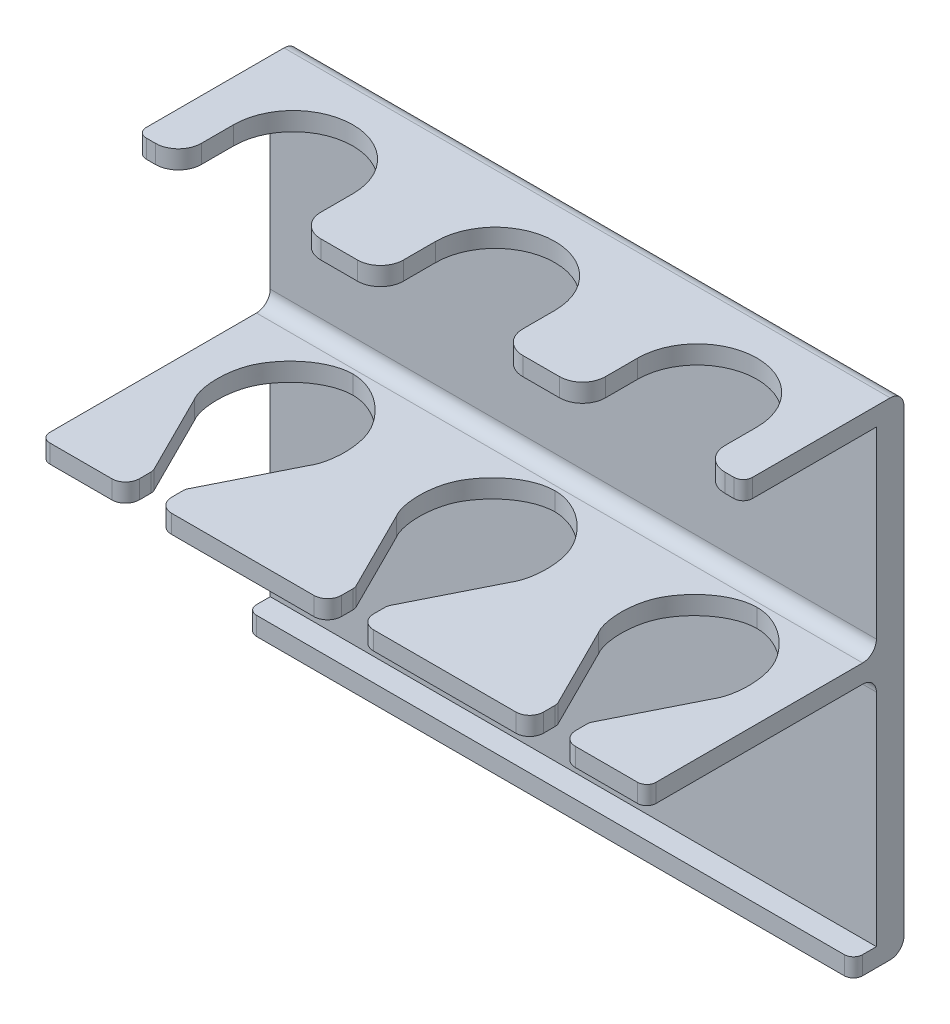
SolidWorks part; units mm, degrees
ref_plane "Front Plane" through (0, 0, 0) normal (0, 0, 1) x (1, 0, 0)
ref_plane "Top Plane" through (0, 0, 0) normal (0, 1, 0) x (1, 0, 0)
ref_plane "Right Plane" through (0, 0, 0) normal (1, 0, 0) x (0, 0, -1)
sketch "Sketch1" plane through (0, 0, 0) normal (0, 0, 1) x (1, 0, 0)
  line L0 (-119, 75.9301) -> (119, 75.9301)
  line L5 (-119, 79.9301) -> (-101, 79.9301)
  line L6 (-101, 79.9301) -> (-75, 79.9301)
  line L7 (-119, 75.9301) -> (-119, 32.9301)
  line L8 (-119, 32.9301) -> (-119, 28.9301)
  line L9 (-119, 28.9301) -> (-119, -22.0699)
  line L10 (-119, -22.0699) -> (-119, -26.0699)
  line L11 (-119, 32.9301) -> (119, 32.9301)
  line L12 (-119, 28.9301) -> (119, 28.9301)
  line L13 (-119, -22.0699) -> (119, -22.0699)
  line L14 (-119, -26.0699) -> (119, -26.0699)
  line L15 (-119, 79.9301) -> (-119, -26.0699)
  line L16 (-119, 79.9301) -> (119, 79.9301)
  line L17 (-119, -26.0699) -> (119, -26.0699)
  line L18 (119, 79.9301) -> (119, -26.0699)
  line L19 (-75, 79.9301) -> (-57, 79.9301)
  line L20 (-57, 79.9301) -> (-31, 79.9301)
  line L21 (-31, 79.9301) -> (-13, 79.9301)
  line L22 (-13, 79.9301) -> (13, 79.9301)
  line L23 (13, 79.9301) -> (31, 79.9301)
  line L24 (31, 79.9301) -> (57, 79.9301)
  line L25 (57, 79.9301) -> (57.0779, 79.9301)
  line L26 (57.0779, 79.9301) -> (75, 79.9301)
  line L27 (75, 79.9301) -> (101, 79.9301)
  point P0 (0, 0)
  dimension "D1" = 238
  dimension "D2" = 4
  dimension "D3" = 43
  dimension "D4" = 4
  dimension "D5" = 51
  dimension "D6" = 4
  dimension "D7" = 18
  dimension "D8" = 26
  dimension "D9" = 18
  dimension "D10" = 26
  dimension "D11" = 18
  dimension "D12" = 26
  dimension "D13" = 18
  dimension "D14" = 26
  dimension "D15" = 18
  dimension "D16" = 26
  dimension "D17" = 18
extrude "Boss-Extrude1" add sketch "Sketch1" along normal blind 6 contours L18 L0 L7 L11 | L18 L16 L6 L5 L15 L0 | L18 L11 L8 L12 | L18 L12 L9 L13 | L18 L13 L10 L14
sketch "Sketch2" plane through (0, 0, 0) normal (0, 0, 1) x (1, 0, 0)
  line L0 (-119, 79.9301) -> (119, 79.9301)
  line L1 (119, 79.9301) -> (119, 75.9301)
  line L2 (119, 79.9301) -> (119, -26.0699) construction
  line L3 (119, 75.9301) -> (-119, 75.9301)
  line L4 (-119, 79.9301) -> (-119, -26.0699) construction
  line L5 (-119, 75.9301) -> (-119, 79.9301)
  dimension "D1" = 4
extrude "Boss-Extrude2" add sketch "Sketch2" along normal blind 35
ref_plane "Plane1" through (0, 79.9301, 0) normal (0, 1, 0) x (1, 0, 0)
sketch "Sketch3" plane through (0, 79.9301, 0) normal (0, 1, 0) x (1, 0, 0)
  line L0 (-119, -35) -> (-101, -35)
  line L1 (119, -35) -> (-119, -35) construction
  line L2 (-101, -35) -> (-75, -35)
  line L3 (-75, -35) -> (-57, -35)
  line L4 (-57, -35) -> (-31, -35)
  line L5 (-31, -35) -> (-13, -35)
  line L6 (-13, -35) -> (13, -35)
  line L7 (13, -35) -> (31, -35)
  line L8 (31, -35) -> (57, -35)
  line L9 (57, -35) -> (75, -35)
  line L10 (75, -35) -> (101, -35)
  line L11 (101, -35) -> (119, -35)
  line L12 (-101, -35) -> (-101, -23)
  line L13 (-75, -35) -> (-75, -23)
  line L14 (-101, -23) -> (-75, -23) construction
  line L16 (-57, -35) -> (-57, -23)
  line L17 (-31, -35) -> (-31, -23)
  line L18 (-13, -35) -> (-13, -23)
  line L19 (13, -35) -> (13, -23)
  line L20 (31, -35) -> (31, -23)
  line L21 (57, -35) -> (57, -23)
  line L22 (75, -35) -> (75, -23)
  line L23 (101, -35) -> (101, -23)
  arc A0 (-101, -23) -> (-75, -23) centre (-88, -23) cw
  arc A1 (-57, -23) -> (-31, -23) centre (-44, -23) cw
  arc A2 (13, -23) -> (-13, -23) centre (0, -23) ccw
  arc A3 (57, -23) -> (31, -23) centre (44, -23) ccw
  arc A4 (101, -23) -> (75, -23) centre (88, -23) ccw
  dimension "D1" = 18
  dimension "D2" = 26
  dimension "D3" = 18
  dimension "D4" = 26
  dimension "D5" = 18
  dimension "D6" = 26
  dimension "D7" = 18
  dimension "D8" = 26
  dimension "D9" = 18
  dimension "D10" = 26
  dimension "D11" = 12
  dimension "D12" = 12
extrude "Cut-Extrude1" cut sketch "Sketch3" against normal blind 6 contours A0 L14 | L14 L12 L2 L13 | A1 L16 L4 L17 | L19 A2 L18 L6 | L21 A3 L20 L8 | L23 A4 L22 L10
fillet "Fillet1" radius 5 12 edges at (-119, 77.9301, 35) (101, 77.9301, 35) (57, 77.9301, 35) (119, 77.9301, 35) (75, 77.9301, 35) (31, 77.9301, 35) (13, 77.9301, 35) (-31, 77.9301, 35) (-13, 77.9301, 35) (-57, 77.9301, 35) (-75, 77.9301, 35) (-101, 77.9301, 35)
ref_plane "Plane2" through (0, 32.9301, 0) normal (0, 1, 0) x (1, 0, 0)
sketch "Sketch4" plane through (0, 32.9301, 0) normal (0, 1, 0) x (1, 0, 0)
  line L0 (-119, 0) -> (-119, -64)
  line L1 (-119, -64) -> (119, -64)
  line L2 (119, -64) -> (119, 0)
  line L3 (119, 0) -> (-119, 0)
  dimension "D1" = 64
extrude "Boss-Extrude3" add sketch "Sketch4" against normal blind 4
sketch "Sketch5" plane through (0, 32.9301, 0) normal (0, 1, 0) x (1, 0, 0)
  line L4 (-40.5, -50) -> (-40.5, -56)
  line L5 (-84.5, -50) -> (-75.5, -32)
  line L24 (-91.5, -50) -> (-100.5, -32)
  line L84 (-84.5, -56) -> (-91.5, -56)
  line L86 (-84.5, -50) -> (-84.5, -56)
  line L87 (-91.5, -50) -> (-91.5, -56)
  line L88 (3.5, -50) -> (12.5, -32)
  line L92 (-47.5, -50) -> (-47.5, -56)
  line L93 (-47.5, -56) -> (-40.5, -56)
  line L94 (-40.5, -50) -> (-31.5, -32)
  line L95 (-47.5, -50) -> (-56.5, -32)
  line L96 (-3.5, -50) -> (-12.5, -32)
  line L97 (3.5, -56) -> (-3.5, -56)
  line L98 (3.5, -50) -> (3.5, -56)
  line L99 (-3.5, -50) -> (-3.5, -56)
  arc A0 (-75, -23) -> (-101, -23) centre (-88, -23) ccw construction
  spline S0 degree 3 poles (-100.5, -32) (-102.1185, -29.3564) (-102.6081, -22.1569) (-97.2689, -13.4239) (-92.1611, -10.0225) (-88, -10) knots 0 0 0 0 0.224491 0.274489 0.499981 0.499981 0.499981 0.499981
  spline S1 degree 3 poles (-75.5, -32) (-73.8815, -29.3564) (-73.3919, -22.1569) (-78.7311, -13.4239) (-83.8389, -10.0225) (-88, -10) knots 0 0 0 0 0.224491 0.274489 0.499981 0.499981 0.499981 0.499981
  spline S2 degree 3 poles (-56.5, -32) (-58.1185, -29.3564) (-58.6081, -22.1569) (-53.2689, -13.4239) (-48.1611, -10.0225) (-44, -10) knots 0 0 0 0 0.224491 0.274489 0.499981 0.499981 0.499981 0.499981
  spline S3 degree 3 poles (-31.5, -32) (-29.8815, -29.3564) (-29.3919, -22.1569) (-34.7311, -13.4239) (-39.8389, -10.0225) (-44, -10) knots 0 0 0 0 0.224491 0.274489 0.499981 0.499981 0.499981 0.499981
  spline S4 degree 3 poles (-12.5, -32) (-14.1185, -29.3564) (-14.6081, -22.1569) (-9.2689, -13.4239) (-4.1611, -10.0225) (0, -10) knots 0 0 0 0 0.224491 0.274489 0.499981 0.499981 0.499981 0.499981
  spline S5 degree 3 poles (12.5, -32) (14.1185, -29.3564) (14.6081, -22.1569) (9.2689, -13.4239) (4.1611, -10.0225) (0, -10) knots 0 0 0 0 0.224491 0.274489 0.499981 0.499981 0.499981 0.499981
ref_plane "Plane3" through (0, -22.0699, 0) normal (0, 1, 0) x (1, 0, 0)
sketch "Sketch6" plane through (0, -22.0699, 0) normal (0, 1, 0) x (1, 0, 0)
  line L0 (-119, 0) -> (-119, -11)
  line L1 (-119, -30) -> (-119, 0) construction
  line L2 (-119, -11) -> (119, -11)
  line L3 (119, -30) -> (119, 0) construction
  line L4 (119, -11) -> (119, 0)
  line L5 (119, 0) -> (-119, 0)
  dimension "D1" = 11
extrude "Boss-Extrude4" add sketch "Sketch6" against normal blind 4
extrude "Cut-Extrude2" cut sketch "Sketch5" against normal blind 10
sketch "Sketch8" plane through (0, 0, 0) normal (0, 1, 0) x (1, 0, 0)
  line L0 (-119, -64) -> (119, -64) construction
  line L1 (-119, -64) -> (119, -64)
  line L2 (-119, -64) -> (-119, -56)
  line L3 (-119, -56) -> (119, -56)
  line L4 (119, -64) -> (119, -56)
  line L5 (-119, -6) -> (-119, -64) construction
  line L6 (119, -64) -> (119, -6) construction
  dimension "D1" = 8
extrude "Cut-Extrude3" cut sketch "Sketch8" along normal blind 60
fillet "Fillet2" radius 3 6 edges at (-84.5, 30.9301, 56) (3.5, 30.9301, 56) (-3.5, 30.9301, 56) (-40.5, 30.9301, 56) (-47.5, 30.9301, 56) (-91.5, 30.9301, 56)
fillet "Fillet3" radius 2 6 edges at (-3.5, 30.9301, 50) (-47.5, 30.9301, 50) (-91.5, 30.9301, 50) (3.5, 30.9301, 50) (-40.5, 30.9301, 50) (-84.5, 30.9301, 50)
fillet "Fillet4" radius 3 4 edges at (0, 28.9301, 6) (0, 79.9301, 0) (0, 32.9301, 6) (0, -26.0699, 0)
sketch "Sketch9" plane through (0, 0, 0) normal (0, 1, 0) x (1, 0, 0)
  line L0 (-110, -35) -> (-110, -70.5707)
  line L1 (-106, -35) -> (-114, -35) construction
  line L2 (-110, -70.5707) -> (-110, 17.336)
  line L3 (-110, 17.336) -> (-146.3557, 17.336)
  line L4 (-146.3557, 17.336) -> (-144.3123, -70.5707)
  line L5 (-144.3123, -70.5707) -> (-110, -70.5707)
  line L6 (22, -35) -> (22, -79.2422)
  line L7 (26, -35) -> (18, -35) construction
  line L8 (22, -79.2422) -> (136.2216, -79.2422)
  line L9 (136.2216, -79.2422) -> (136.2216, 30.5546)
  line L10 (136.2216, 30.5546) -> (22, 30.5546)
  line L11 (22, 30.5546) -> (22, -35)
extrude "Cut-Extrude4" cut sketch "Sketch9" against normal mid plane 300 contours L4 L5 L0 L2 L3 | L10 L11 L6 L8 L9
fillet "Fillet5" radius 2 6 edges at (22, -24.0699, 11) (22, 30.9301, 56) (22, 77.9301, 35) (-110, -24.0699, 11) (-110, 77.9301, 35) (-110, 30.9301, 56)
